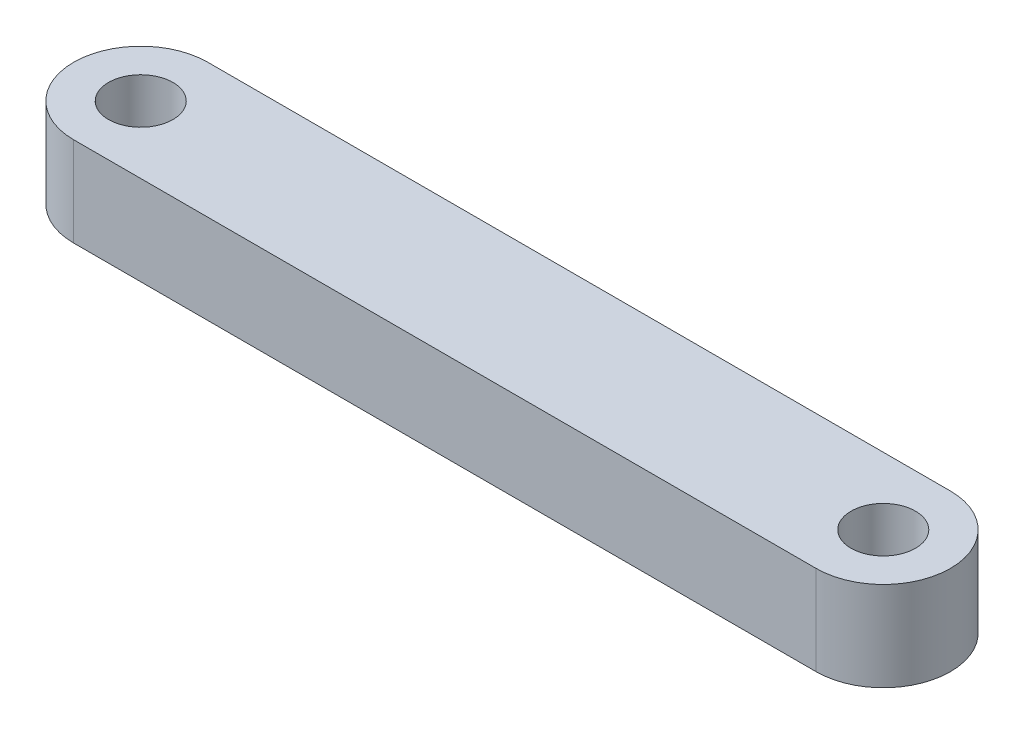
SolidWorks part; units mm, degrees
ref_plane "Front Plane" through (0, 0, 0) normal (0, 0, 1) x (1, 0, 0)
ref_plane "Top Plane" through (0, 0, 0) normal (0, 1, 0) x (1, 0, 0)
ref_plane "Right Plane" through (0, 0, 0) normal (1, 0, 0) x (0, 0, -1)
sketch "Sketch1" plane through (0, 0, 0) normal (0, 1, 0) x (1, 0, 0)
  line L0 (0, 0) -> (-52.705, 0) construction
  line L1 (0, -4.7625) -> (-52.705, -4.7625)
  line L2 (0, 4.7625) -> (-52.705, 4.7625)
  arc A0 (0, -4.7625) -> (0, 4.7625) centre (0, 0) ccw
  arc A1 (-52.705, 4.7625) -> (-52.705, -4.7625) centre (-52.705, 0) ccw
  circle A2 centre (0, 0) radius 2.286
  circle A3 centre (-52.705, 0) radius 2.286
  point P3 (-26.3525, 0)
  dimension "D2" = 4.7625
  dimension "D3" = 4.572
  dimension "D1" = 52.705
extrude "Boss-Extrude1" add sketch "Sketch1" along normal blind 6.35
